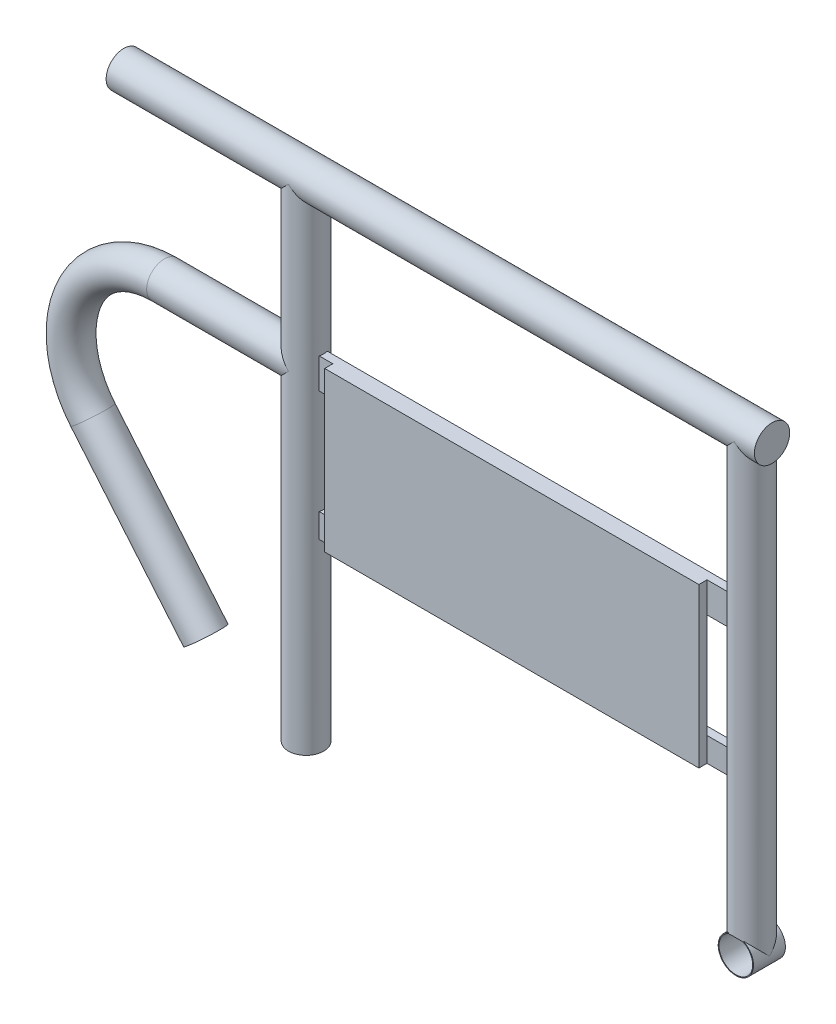
SolidWorks part; units mm, degrees
ref_plane "Front Plane" through (0, 0, 0) normal (0, 0, 1) x (1, 0, 0)
ref_plane "Top Plane" through (0, 0, 0) normal (0, 1, 0) x (1, 0, 0)
ref_plane "Right Plane" through (0, 0, 0) normal (1, 0, 0) x (0, 0, -1)
sketch "Sketch1" plane through (0, 0, 0) normal (0, 1, 0) x (1, 0, 0)
  circle A0 centre (0, 0) radius 11.065
  circle A1 centre (279.4, 0) radius 11.065
  dimension "D1" = 22.13
  dimension "D2" = 22.13
  dimension "D3" = 279.4
extrude "Extrude1" add sketch "Sketch1" along normal blind 279.4
sketch "Sketch2" plane through (0, 0, 0) normal (1, 0, 0) x (0, 0, -1)
  line L0 (11.065, 279.4) -> (-11.065, 279.4) construction
  circle A0 centre (0, 279.4) radius 11.065
extrude "Extrude2" add sketch "Sketch2" along normal blind 292.1 and the other way blind 114.3
sketch "Sketch3" plane through (-114.3, 0, 0) normal (-1, 0, 0) x (0, 0, 1)
  circle A0 centre (0, 177.8) radius 11.065
  circle A1 centre (0, 279.4) radius 11.065 construction
  dimension "D1" = 101.6
extrude "Extrude3" add sketch "Sketch3" against normal blind 114.3
sketch "Sketch5" plane through (0, 0, 0) normal (0, 0, 1) x (1, 0, 0)
  line L0 (-114.3, 188.865) -> (-114.3, 166.735) construction
  line L1 (-139.7, 188.865) -> (-88.9, 188.865)
  line L2 (-139.7, 188.865) -> (-139.7, 166.735)
  line L3 (-139.7, 166.735) -> (-88.9, 166.735)
  line L4 (-88.9, 188.865) -> (-88.9, 166.735)
  line L5 (-139.7, 188.865) -> (-88.9, 166.735) construction
  line L6 (-139.7, 166.735) -> (-88.9, 188.865) construction
  line L7 (-114.3, 166.735) -> (-11.065, 166.735) construction
  point P0 (-114.3, 177.8)
  dimension "D1" = 25.4
extrude "Extrude5" cut sketch "Sketch5" against normal through all and the other way through all
sketch "Sketch7" plane through (-88.9, 0, 0) normal (-1, 0, 0) x (0, 0, 1)
  line L0 (0, 119.38) -> (28.8371, 119.38)
  circle A0 centre (0, 177.8) radius 11.065
  dimension "D1" = 58.42
revolve "Revolve-Thin3" add sketch "Sketch7" angle 130 about L0 wall 10
sketch "Sketch10" plane through (-95.5145, 113.8298, 0) normal (0.6428, -0.766, 0) x (0.766, 0.6428, 0)
  circle A0 centre (-49.7854, 0) radius 11.065
extrude "Extrude6" add sketch "Sketch10" along normal blind 110.1
sketch "Sketch11" plane through (0, 0, 0) normal (1, 0, 0) x (0, 0, -1)
  line L1 (2.55, 168.275) -> (-2.55, 168.275)
  line L2 (2.55, 168.275) -> (2.55, 187.325)
  line L3 (2.55, 187.325) -> (-2.55, 187.325)
  line L4 (-2.55, 168.275) -> (-2.55, 187.325)
  line L5 (2.55, 168.275) -> (-2.55, 187.325) construction
  line L6 (2.55, 187.325) -> (-2.55, 168.275) construction
  line L7 (2.55, 87.6717) -> (-2.55, 87.6717)
  line L8 (2.55, 87.6717) -> (2.55, 102.8283)
  line L9 (2.55, 102.8283) -> (-2.55, 102.8283)
  line L10 (-2.55, 87.6717) -> (-2.55, 102.8283)
  line L11 (2.55, 87.6717) -> (-2.55, 102.8283) construction
  line L12 (2.55, 102.8283) -> (-2.55, 87.6717) construction
  point P0 (0, 177.8)
  point P6 (0, 95.25)
  dimension "D1" = 19.05
  dimension "D2" = 5.1
  dimension "D3" = 82.55
extrude "Extrude7" add sketch "Sketch11" along normal blind 279.4
sketch "Sketch12" plane through (0, 0, 2.55) normal (0, 0, 1) x (1, 0, 0)
  line L0 (268.6328, 187.325) -> (10.7672, 187.325) construction
  line L1 (19.2926, 187.325) -> (253.8741, 187.325)
  line L2 (19.2926, 187.325) -> (19.2926, 87.6717)
  line L3 (19.2926, 87.6717) -> (253.8741, 87.6717)
  line L4 (253.8741, 187.325) -> (253.8741, 87.6717)
  line L5 (268.6328, 87.6717) -> (10.7672, 87.6717) construction
extrude "Extrude8" add sketch "Sketch12" along normal blind 5.1
sketch "Sketch13" plane through (0, 0, 0) normal (0, 0, 1) x (1, 0, 0)
  line L0 (268.335, 0) -> (290.465, 0) construction
  circle A0 centre (279.4, 0) radius 11.065
  circle A1 centre (279.4, 0) radius 10.565
  dimension "D1" = 0.5
extrude "Extrude9" add sketch "Sketch13" along normal blind 10 and the other way blind 10
sketch "Sketch14" plane through (0, 0, -10) normal (0, 0, -1) x (-1, 0, 0)
  line L0 (-289.965, 0) -> (-268.835, 0) construction
  circle A0 centre (-279.4, 0) radius 10.565
extrude "Extrude10" cut sketch "Sketch14" against normal through all and the other way through all
sketch "Sketch15" plane through (0, 0, 0) normal (0, -1, 0) x (1, 0, 0)
  circle A0 centre (0, 0) radius 11.065
extrude "Extrude11" add sketch "Sketch15" along normal blind 28.4
